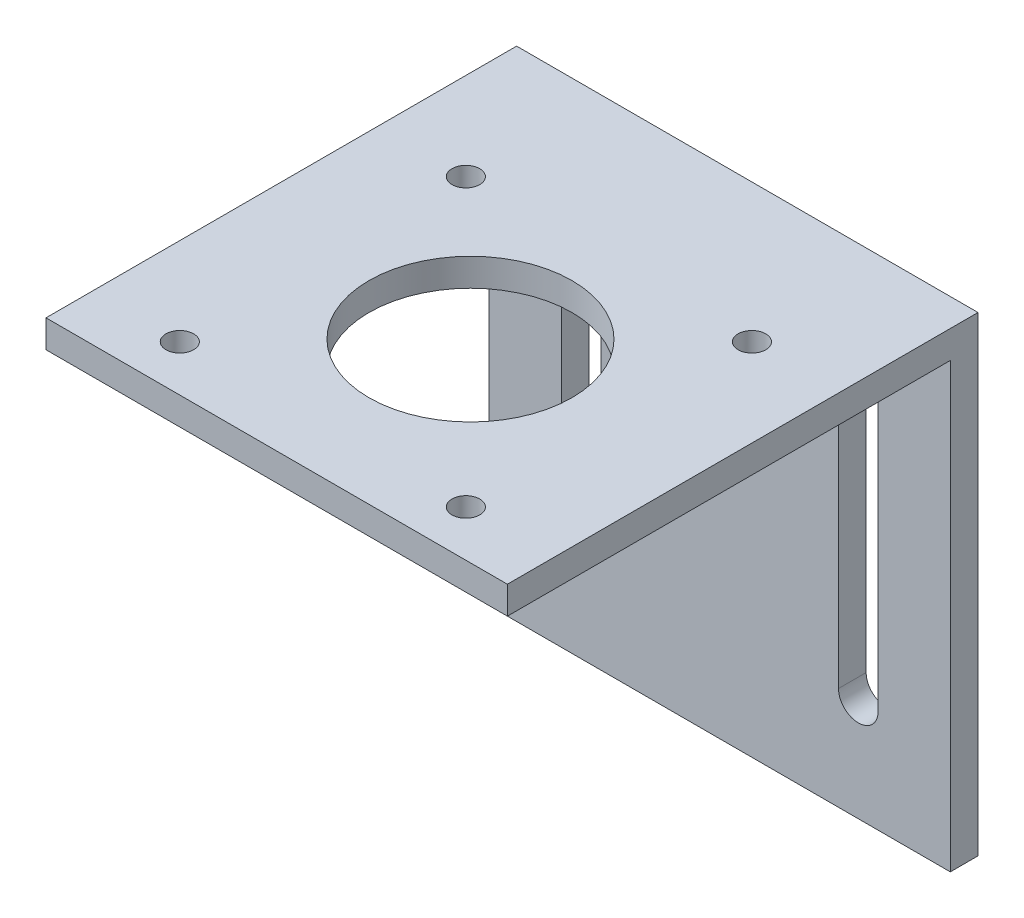
SolidWorks part; units mm, degrees
ref_plane "Front Plane" through (0, 0, 0) normal (0, 0, 1) x (1, 0, 0)
ref_plane "Top Plane" through (0, 0, 0) normal (0, 1, 0) x (1, 0, 0)
ref_plane "Right Plane" through (0, 0, 0) normal (1, 0, 0) x (0, 0, -1)
sketch "Sketch1" plane through (0, 0, 0) normal (0, 0, 1) x (1, 0, 0)
  line L0 (-17.15, 15.35) -> (-17.15, -14.35)
  line L1 (-25, -25.5) -> (25, -25.5)
  line L2 (-25, -25.5) -> (-25, 25.5)
  line L3 (-25, 25.5) -> (25, 25.5)
  line L4 (25, -25.5) -> (25, 25.5)
  line L5 (-25, -25.5) -> (25, 25.5) construction
  line L6 (-25, 25.5) -> (25, -25.5) construction
  line L7 (-12.85, 15.35) -> (-12.85, -14.35)
  line L8 (12.88, 15.35) -> (12.88, -14.35)
  line L9 (17.18, 15.35) -> (17.18, -14.35)
  arc A0 (-17.15, -14.35) -> (-12.85, -14.35) centre (-15, -14.35) ccw
  arc A1 (-17.15, 15.35) -> (-12.85, 15.35) centre (-15, 15.35) cw
  arc A2 (12.88, -14.35) -> (17.18, -14.35) centre (15.03, -14.35) ccw
  arc A3 (12.88, 15.35) -> (17.18, 15.35) centre (15.03, 15.35) cw
  point P0 (0, 0)
  point P12 (-13.35, 17.7945)
  point P13 (-15, -16.5)
  point P20 (15.03, -16.5)
  point P21 (12.88, 0.5)
  point P22 (0, 0)
  point P23 (-15, 17.5)
  point P24 (15.03, 17.5)
  dimension "D6" = 25.73
  dimension "D9" = 34
  dimension "D1" = 51
  dimension "D2" = 50
  dimension "D3" = 7.85
  dimension "D4" = 4.3
  dimension "D5" = 9
  dimension "D7" = 4.3
  dimension "D8" = 34
extrude "Boss-Extrude1" add sketch "Sketch1" along normal blind 3
sketch "Sketch2" plane through (0, 0, 3) normal (0, 0, 1) x (1, 0, 0)
  line L0 (25, -25.5) -> (25, 25.5) construction
  line L1 (-25, 25.5) -> (25, 25.5)
  line L2 (-25, 25.5) -> (-25, 22.5)
  line L3 (-25, 22.5) -> (25, 22.5)
  line L4 (25, 25.5) -> (25, 22.5)
  dimension "D1" = 3
extrude "Boss-Extrude2" add sketch "Sketch2" along normal blind 48
sketch "Sketch3" plane through (0, 22.5, 0) normal (0, -1, 0) x (1, 0, 0)
  line L0 (-25, 51) -> (25, 51) construction
  line L1 (-25, 51) -> (-25, 3) construction
  circle A0 centre (0, 30) radius 11
  circle A1 centre (-15.5, 46) radius 1.5
  circle A2 centre (15.5, 46) radius 1.5
  circle A3 centre (-15.5, 15) radius 1.5
  circle A4 centre (15.5, 15) radius 1.5
  point P9 (0, 51)
  point P13 (0, 0)
  point P14 (0, 0)
  point P15 (0, 0)
  point P16 (0, 0)
  point P19 (-15, 44.1653)
  point P20 (-15, 45.9932)
  point P21 (0, 0)
  dimension "D1" = 22
  dimension "D6" = 3
  dimension "D7" = 9.5
  dimension "D2" = 21
  dimension "D3" = 31
  dimension "D4" = 31
  dimension "D5" = 31
  dimension "D8" = 5
extrude "Cut-Extrude1" cut sketch "Sketch3" against normal through all both and the other way through all
